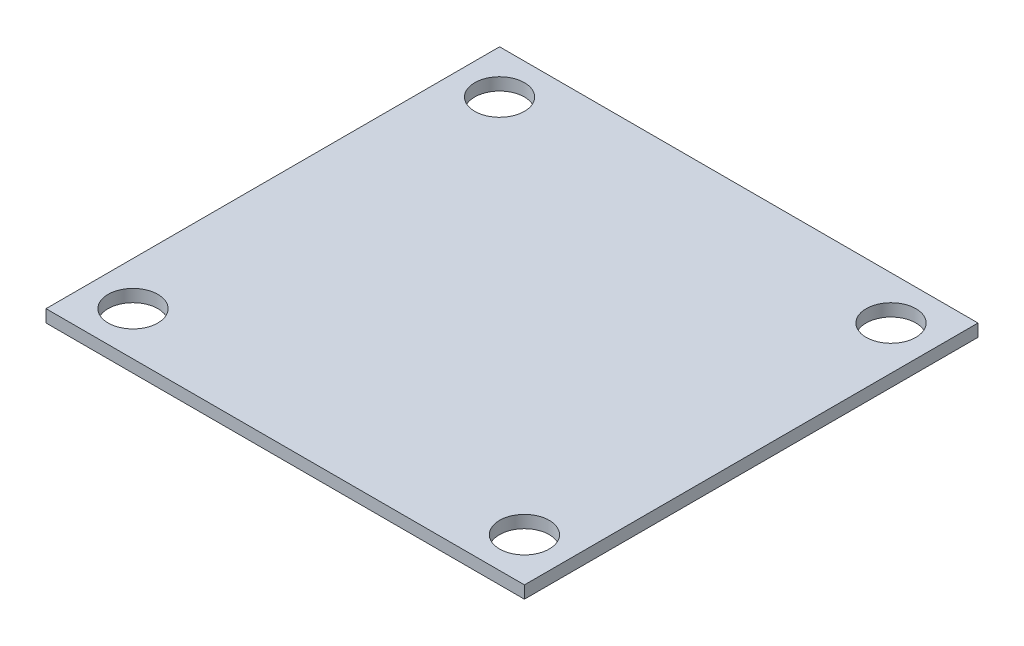
SolidWorks part; units mm, degrees
ref_plane "Alzado" through (0, 0, 0) normal (0, 0, 1) x (1, 0, 0)
ref_plane "Planta" through (0, 0, 0) normal (0, 1, 0) x (1, 0, 0)
ref_plane "Vista lateral" through (0, 0, 0) normal (1, 0, 0) x (0, 0, -1)
sketch "Croquis1" plane through (0, 0, 0) normal (0, 1, 0) x (1, 0, 0)
  line L0 (15.75, 14.75) -> (15.75, 18.25) construction
  line L1 (-19.25, -18.25) -> (19.25, -18.25)
  line L2 (-19.25, -18.25) -> (-19.25, 18.25)
  line L3 (-19.25, 18.25) -> (19.25, 18.25)
  line L4 (19.25, -18.25) -> (19.25, 18.25)
  line L5 (-19.25, -18.25) -> (19.25, 18.25) construction
  line L6 (-19.25, 18.25) -> (19.25, -18.25) construction
  line L7 (15.75, 14.75) -> (19.25, 14.75) construction
  line L8 (-15.75, -14.75) -> (-15.75, -18.25) construction
  line L9 (-15.75, -14.75) -> (-19.25, -14.75) construction
  circle A0 centre (15.75, 14.75) radius 2
  circle A1 centre (-15.75, -14.75) radius 2
  circle A2 centre (15.75, -14.75) radius 2
  circle A3 centre (-15.75, 14.75) radius 2
  point P0 (0, 0)
  dimension "D3" = 4
  dimension "D1" = 36.5
  dimension "D2" = 38.5
  dimension "D4" = 3.5
extrude "Saliente-Extruir1" add sketch "Croquis1" along normal blind 1
